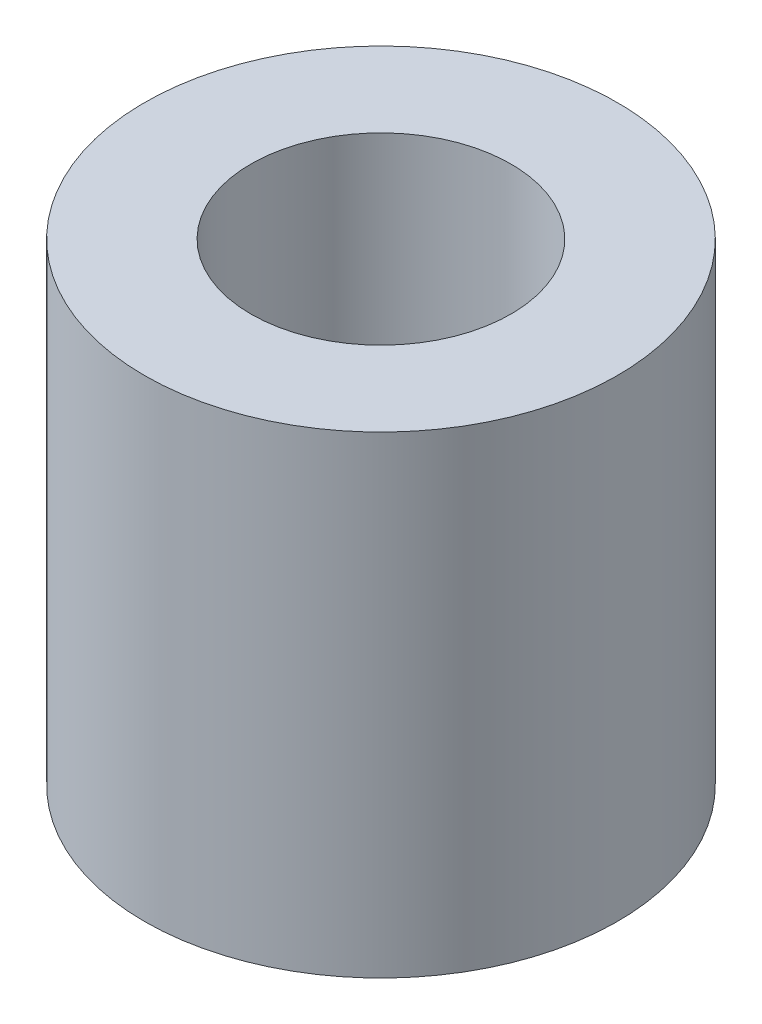
SolidWorks part; units mm, degrees
material "AISI 1020"
ref_plane "Alzado" through (0, 0, 0) normal (0, 0, 1) x (1, 0, 0)
ref_plane "Planta" through (0, 0, 0) normal (0, 1, 0) x (1, 0, 0)
ref_plane "Vista lateral" through (0, 0, 0) normal (1, 0, 0) x (0, 0, -1)
sketch "Croquis2" plane through (0, 0, 0) normal (0, 1, 0) x (1, 0, 0)
  circle A0 centre (0, 0) radius 2
  dimension "D1" = 4
extrude "Saliente-Extruir1" add sketch "Croquis2" along normal blind 4
hole_wizard "Taladro de margen para M21" positions "Croquis3" profile "Croquis4" hole size "M2" standard "ISO"
sketch "Croquis3" plane through (0, 4, 0) normal (0, 1, 0) x (1, 0, 0)
  point P0 (0, 0)
sketch "Croquis4" plane through (0, 4, 0) normal (1, 0, 0) x (0, 0, 1)
  line L0 (0, 0) -> (0, 20.6609)
  line L1 (0, 20.6609) -> (1.1, 20)
  line L2 (1.1, 20) -> (1.1, 0)
  line L5 (1.1, 0) -> (0, 0)
  line L10 (0, 20.6609) -> (-1.1, 20) construction
  line L11 (0, -6.35) -> (0, 107.95) construction
  dimension "Diámetro de taladro" = 2.2
  dimension "Profundidad de taladro" = 20
  dimension "Ángulo de perforador" = 118
